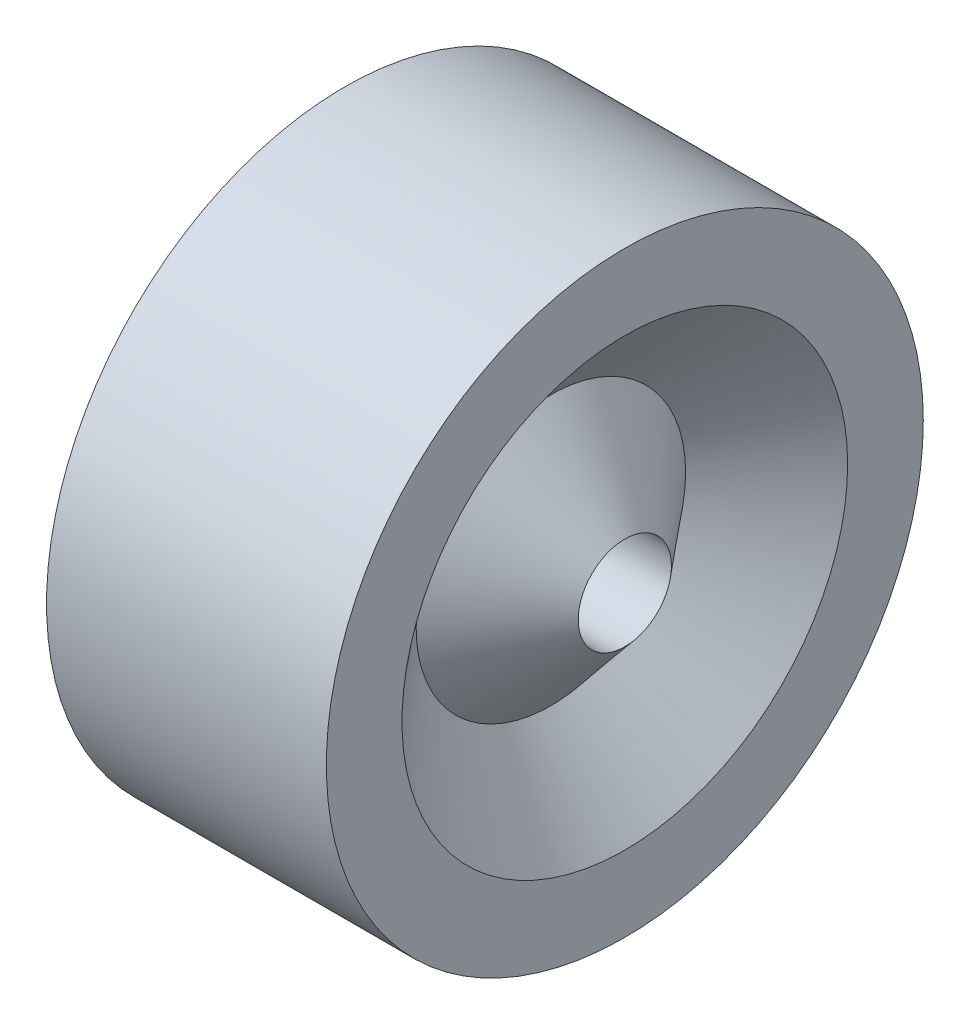
SolidWorks part; units mm, degrees
material "ABS"
ref_plane "Спереди" through (0, 0, 0) normal (0, 0, 1) x (1, 0, 0)
ref_plane "Сверху" through (0, 0, 0) normal (0, 1, 0) x (1, 0, 0)
ref_plane "Справа" through (0, 0, 0) normal (1, 0, 0) x (0, 0, -1)
sketch "Эскиз1" plane through (0, 0, 0) normal (1, 0, 0) x (0, 0, -1)
  circle A0 centre (0, 0) radius 5
  circle A1 centre (0, 0) radius 32
  dimension "D1" = 10
  dimension "D2" = 64
extrude "Бобышка-Вытянуть1" add sketch "Эскиз1" along normal blind 30
sketch "Эскиз2" plane through (30, 0, 0) normal (1, 0, 0) x (0, 0, -1)
  circle A0 centre (0, 0) radius 23.8907
  circle A1 centre (0, 0) radius 5 construction
  circle A2 centre (0, 0) radius 5
extrude "Вырез-Вытянуть1" cut sketch "Эскиз2" against normal blind 10 draft 50
